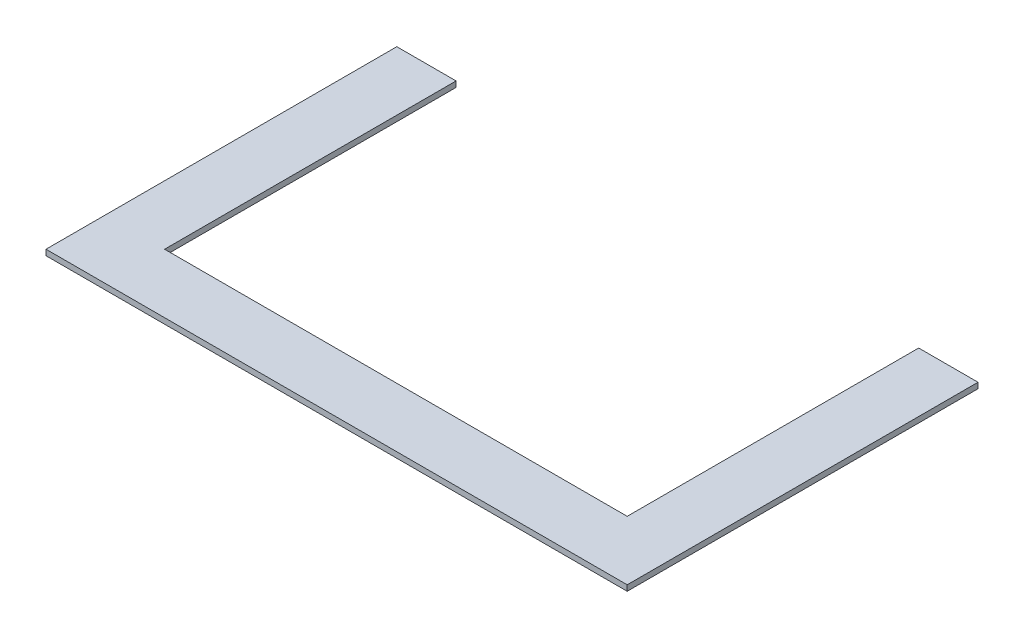
SolidWorks part; units mm, degrees
ref_plane "Front Plane" through (0, 0, 0) normal (0, 0, 1) x (1, 0, 0)
ref_plane "Top Plane" through (0, 0, 0) normal (0, 1, 0) x (1, 0, 0)
ref_plane "Right Plane" through (0, 0, 0) normal (1, 0, 0) x (0, 0, -1)
sketch "Sketch1" plane through (0, 0, 0) normal (0, 1, 0) x (1, 0, 0)
  line L0 (51.1142, 70.5031) -> (70.2658, 70.5031)
  line L1 (70.2658, 70.5031) -> (70.2658, -42.8063)
  line L2 (70.2658, -42.8063) -> (-117.4656, -42.8063)
  line L3 (-117.4656, -42.8063) -> (-117.4656, 70.5031)
  line L4 (-117.4656, 70.5031) -> (-98.314, 70.5031)
  line L5 (-98.314, 70.5031) -> (-98.314, -23.6547)
  line L6 (-98.314, -23.6547) -> (51.1142, -23.6547)
  line L7 (51.1142, -23.6547) -> (51.1142, 70.5031)
  dimension "D1" = 187.7314
  dimension "D2" = 113.3094
  dimension "D3" = 113.3094
  dimension "D4" = 94.1578
  dimension "D5" = 94.1578
  dimension "D6" = 19.1516
  dimension "D7" = 19.1516
  dimension "D8" = 149.4282
extrude "Boss-Extrude1" add sketch "Sketch1" along normal blind 1.8288 contours L5 L6 L7 L0 L1 L2 L3 L4
